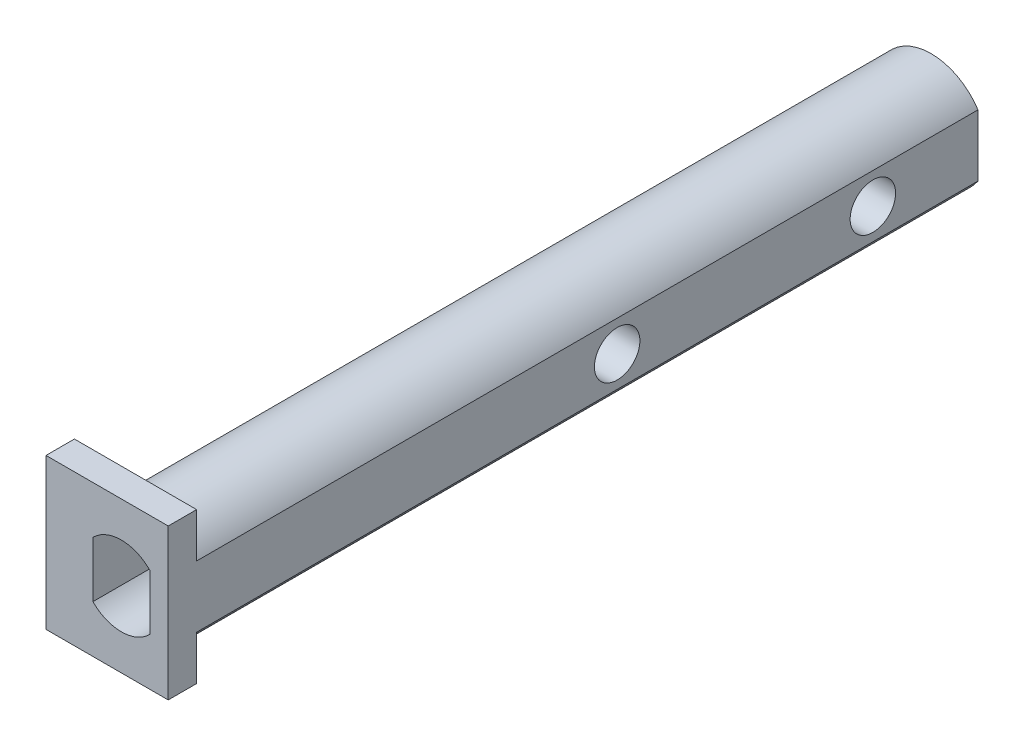
SolidWorks part; units mm, degrees
ref_plane "Ön Düzlem" through (0, 0, 0) normal (0, 0, 1) x (1, 0, 0)
ref_plane "Üst Düzlem" through (0, 0, 0) normal (0, 1, 0) x (1, 0, 0)
ref_plane "Sağ Düzlem" through (0, 0, 0) normal (1, 0, 0) x (0, 0, -1)
sketch "Çizim1" plane through (0, 0, 0) normal (0, 0, 1) x (1, 0, 0)
  line L1 (5.3033, -5.3033) -> (-5.3033, -5.3033)
  line L2 (5.3033, -5.3033) -> (5.3033, 5.3033)
  line L3 (5.3033, 5.3033) -> (-5.3033, 5.3033)
  line L4 (-5.3033, -5.3033) -> (-5.3033, 5.3033)
  line L5 (5.3033, -5.3033) -> (-5.3033, 5.3033) construction
  line L6 (5.3033, 5.3033) -> (-5.3033, -5.3033) construction
  circle A0 centre (0, 0) radius 7.5 construction
  dimension "D1" = 15
extrude "Yükseklik-Ekstrüzyon1" add sketch "Çizim1" along normal blind 2
sketch "Çizim2" plane through (0, 0, 0) normal (0, 0, -1) x (-1, 0, 0)
  circle A0 centre (0, 0) radius 3.95
  dimension "D1" = 7.9
extrude "Yükseklik-Ekstrüzyon2" add sketch "Çizim2" along normal blind 55 contours A0
sketch "Çizim3" plane through (0, 0, 2) normal (0, 0, 1) x (1, 0, 0)
  line L0 (-2, -1.9596) -> (-2, 1.9596)
  line L1 (2, -1.9596) -> (2, 1.9596)
  arc A0 (-2, -1.9596) -> (2, -1.9596) centre (0, 0) ccw
  arc A1 (2, 1.9596) -> (-2, 1.9596) centre (0, 0) ccw
  dimension "D1" = 5.6
  dimension "D2" = 2
  dimension "D3" = 2
extrude "Kes-Ekstrüzyon1" cut sketch "Çizim3" against normal blind 10
sketch "Çizim5" plane through (0, 0, 0) normal (1, 0, 0) x (0, 0, -1)
  line L0 (55, -3.95) -> (55, 3.95) construction
  circle A0 centre (29.6, 0) radius 1.6
  circle A1 centre (47.6, 0) radius 1.6
  dimension "D3" = 3.2
  dimension "D1" = 7.4
  dimension "D2" = 18
extrude "Kes-Ekstrüzyon3" cut sketch "Çizim5" against normal mid plane 52
sketch "Çizim8" plane through (0, 0, -55) normal (0, 0, -1) x (-1, 0, 0)
  line L0 (-3.3, 6.8105) -> (-3.3, -6.8105)
  line L1 (-3.3, 6.8105) -> (-8.3, 6.8105)
  line L2 (-8.3, 6.8105) -> (-8.3, -6.8105)
  line L3 (-8.3, -6.8105) -> (-3.3, -6.8105)
  circle A0 centre (0, 0) radius 3.95 construction
  point P2 (-3.3, 0)
  dimension "D1" = 5
  dimension "D2" = 3.3
  dimension "D3" = 6.8105
extrude "Kes-Ekstrüzyon4" cut sketch "Çizim8" against normal through all
